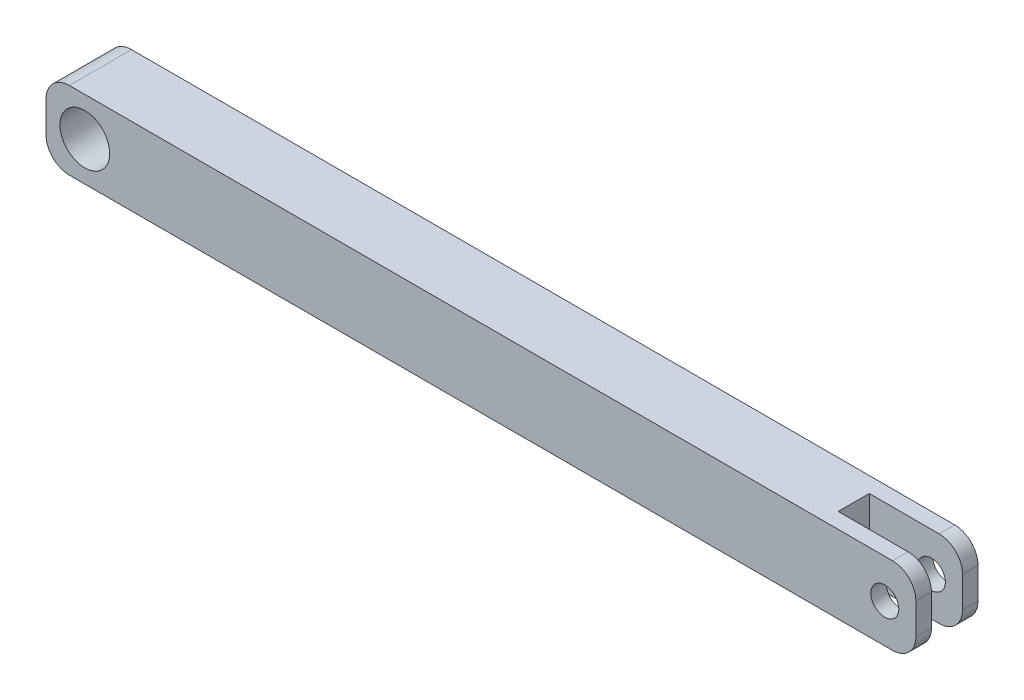
SolidWorks part; units mm, degrees
ref_plane "前视基准面" through (0, 0, 0) normal (0, 0, 1) x (1, 0, 0)
ref_plane "上视基准面" through (0, 0, 0) normal (0, 1, 0) x (1, 0, 0)
ref_plane "右视基准面" through (0, 0, 0) normal (1, 0, 0) x (0, 0, -1)
other "Configuration Table"
sketch "草图5" plane through (0, 0, 0) normal (0, 1, 0) x (1, 0, 0)
  line L0 (0, 0) -> (0, -3)
  line L4 (56, -3) -> (56, 0)
  line L8 (56, 0) -> (0, 0)
  line L9 (0, -3) -> (56, -3)
  dimension "D6" = 3
  dimension "D1" = 56
  dimension "D5" = 3
extrude "凸台-拉伸1" add sketch "草图5" along normal blind 5
sketch "草图6" plane through (0, 0, 3) normal (0, 0, 1) x (1, 0, 0)
  line L2 (0, 5) -> (0, 0) construction
  line L3 (0, 5) -> (56, 5) construction
  circle A0 centre (2.5, 2.5) radius 1.6
  dimension "D1" = 3.2
  dimension "D2" = 2.5
  dimension "D3" = 2.5
extrude "切除-拉伸1" cut sketch "草图6" against normal up to next
sketch "草图7" plane through (0, 0, 0) normal (0, 0, 1) x (1, 0, 0)
  line L0 (56, 5) -> (56, 0) construction
  circle A0 centre (54, 2.5) radius 0.9
  point P6 (56, 2.5)
  dimension "D1" = 1.8
  dimension "D2" = 2
extrude "切除-拉伸2" cut sketch "草图7" along normal up to next
fillet "圆角1" radius 1.5 4 edges at (56, 5, 1.5) (56, 0, 1.5) (0, 0, 1.5) (0, 5, 1.5)
sketch "草图8" plane through (0, 5, 0) normal (0, 1, 0) x (1, 0, 0)
  line L0 (56, 0) -> (56, -3) construction
  line L1 (56, -0.7) -> (50, -0.7)
  line L2 (56, -0.7) -> (56, -2.3)
  line L3 (56, -2.3) -> (50, -2.3)
  line L4 (50, -0.7) -> (50, -2.3)
  point P6 (56, -1.5)
  dimension "D1" = 1.6
  dimension "D2" = 6
extrude "切除-拉伸3" cut sketch "草图8" against normal blind 10
sketch "草图10" plane through (0, 0, 3) normal (0, 0, 1) x (1, 0, 0)
  line L4 (56, 1.5) -> (56, 3.5)
  line L5 (54.5, 5) -> (1.5, 5)
  line L6 (0, 3.5) -> (0, 1.5)
  line L7 (1.5, 0) -> (54.5, 0)
  line L8 (56, 1.5) -> (56, 3.5)
  line L9 (54.5, 5) -> (1.5, 5)
  line L10 (0, 3.5) -> (0, 1.5)
  line L11 (1.5, 0) -> (54.5, 0)
  circle A0 centre (2.5, 2.5) radius 1.6 construction
  circle A1 centre (2.5, 2.5) radius 1.6
  circle A2 centre (54, 2.5) radius 0.9 construction
  circle A3 centre (54, 2.5) radius 0.9
  arc A4 (56, 3.5) -> (54.5, 5) centre (54.5, 3.5) ccw
  arc A5 (1.5, 5) -> (0, 3.5) centre (1.5, 3.5) ccw
  arc A6 (0, 1.5) -> (1.5, 0) centre (1.5, 1.5) ccw
  arc A7 (54.5, 0) -> (56, 1.5) centre (54.5, 1.5) ccw
  arc A8 (56, 3.5) -> (54.5, 5) centre (54.5, 3.5) ccw
  arc A9 (1.5, 5) -> (0, 3.5) centre (1.5, 3.5) ccw
  arc A10 (0, 1.5) -> (1.5, 0) centre (1.5, 1.5) ccw
  arc A11 (54.5, 0) -> (56, 1.5) centre (54.5, 1.5) ccw
  dimension "D1" = 0
extrude "凸台-拉伸2" add sketch "草图10" along normal blind 0.5
sketch "草图11" plane through (0, 0, 0) normal (0, 0, -1) x (-1, 0, 0)
  line L4 (-1.5, 5) -> (-54.5, 5)
  line L5 (-56, 3.5) -> (-56, 1.5)
  line L6 (-54.5, 0) -> (-1.5, 0)
  line L7 (0, 1.5) -> (0, 3.5)
  line L8 (-1.5, 5) -> (-54.5, 5)
  line L9 (-56, 3.5) -> (-56, 1.5)
  line L10 (-54.5, 0) -> (-1.5, 0)
  line L11 (0, 1.5) -> (0, 3.5)
  circle A0 centre (-54, 2.5) radius 0.9 construction
  circle A1 centre (-2.5, 2.5) radius 1.6 construction
  circle A2 centre (-54, 2.5) radius 0.9
  circle A3 centre (-2.5, 2.5) radius 1.6
  arc A4 (-54.5, 5) -> (-56, 3.5) centre (-54.5, 3.5) ccw
  arc A5 (-56, 1.5) -> (-54.5, 0) centre (-54.5, 1.5) ccw
  arc A6 (-1.5, 0) -> (0, 1.5) centre (-1.5, 1.5) ccw
  arc A7 (0, 3.5) -> (-1.5, 5) centre (-1.5, 3.5) ccw
  arc A8 (-54.5, 5) -> (-56, 3.5) centre (-54.5, 3.5) ccw
  arc A9 (-56, 1.5) -> (-54.5, 0) centre (-54.5, 1.5) ccw
  arc A10 (-1.5, 0) -> (0, 1.5) centre (-1.5, 1.5) ccw
  arc A11 (0, 3.5) -> (-1.5, 5) centre (-1.5, 3.5) ccw
  dimension "D1" = 0
extrude "凸台-拉伸3" add sketch "草图11" along normal blind 0.5
sketch "草图12" plane through (0, 5, 0) normal (0, 1, 0) x (1, 0, 0)
  line L1 (56.8423, -2.5) -> (50, -2.5)
  line L2 (56.8423, -2.5) -> (56.8423, -0.5)
  line L3 (56.8423, -0.5) -> (50, -0.5)
  line L4 (50, -2.5) -> (50, -0.5)
  line L5 (56.8423, -2.5) -> (50, -0.5) construction
  line L6 (56.8423, -0.5) -> (50, -2.5) construction
  line L7 (54.5, -0.7) -> (50, -0.7) construction
  line L8 (50, -2.3) -> (54.5, -2.3) construction
  point P0 (53.4212, -1.5)
  dimension "D1" = 0.2
  dimension "D2" = 0.2
extrude "切除-拉伸4" cut sketch "草图12" against normal blind 10
